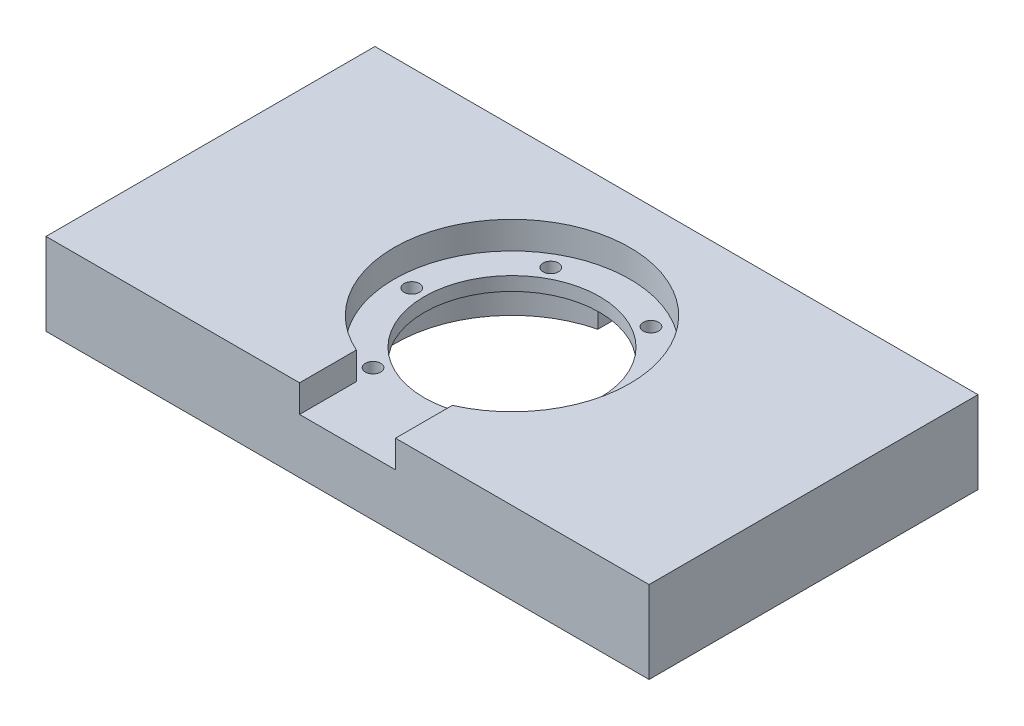
SolidWorks part; units mm, degrees
ref_plane "Front Plane" through (0, 0, 0) normal (0, 0, 1) x (1, 0, 0)
ref_plane "Top Plane" through (0, 0, 0) normal (0, 1, 0) x (1, 0, 0)
ref_plane "Right Plane" through (0, 0, 0) normal (1, 0, 0) x (0, 0, -1)
sketch "Sketch1" plane through (0, 0, 0) normal (0, 1, 0) x (1, 0, 0)
  line L1 (110, -60) -> (-110, -60)
  line L2 (110, -60) -> (110, 60)
  line L3 (110, 60) -> (-110, 60)
  line L4 (-110, -60) -> (-110, 60)
  line L5 (110, -60) -> (-110, 60) construction
  line L6 (110, 60) -> (-110, -60) construction
  circle A0 centre (0, 0) radius 43
  dimension "D1" = 86
  dimension "D2" = 120
  dimension "D3" = 220
extrude "Boss-Extrude1" add sketch "Sketch1" along normal blind 10
sketch "Sketch2" plane through (0, 0, 0) normal (0, -1, 0) x (1, 0, 0)
  line L1 (-110, 60) -> (110, 60)
  line L2 (-110, 60) -> (-110, -60)
  line L3 (-110, -60) -> (110, -60)
  line L4 (110, 60) -> (110, -60)
  circle A0 centre (18.1221, 32.2581) radius 2.8
  circle A1 centre (36.9974, 0.4348) radius 2.8
  circle A2 centre (18.8753, -31.8233) radius 2.8
  circle A3 centre (-18.1221, -32.2581) radius 2.8
  circle A4 centre (-36.9974, -0.4348) radius 2.8
  circle A5 centre (-18.8753, 31.8233) radius 2.8
  point P21 (0, 0)
  dimension "D1" = 5.6
  dimension "D2" = 37
  dimension "D3" = 6
extrude "Boss-Extrude2" add sketch "Sketch2" along normal blind 20
sketch "Sketch3" plane through (0, 0, 60) normal (0, 0, 1) x (1, 0, 0)
  line L0 (-110, 10) -> (110, 10) construction
  line L1 (-17.5, 0) -> (17.5, 0)
  line L2 (-17.5, 0) -> (-17.5, 10)
  line L3 (-17.5, 10) -> (17.5, 10)
  line L4 (17.5, 0) -> (17.5, 10)
  line L5 (-17.5, 0) -> (17.5, 10) construction
  line L6 (-17.5, 10) -> (17.5, 0) construction
  point P0 (0, 5)
  dimension "D1" = 35
  dimension "D2" = 10
extrude "Cut-Extrude1" cut sketch "Sketch3" against normal up to next
sketch "Sketch4" plane through (0, 0, 0) normal (0, 1, 0) x (1, 0, 0)
  circle A0 centre (0, 0) radius 32
  dimension "D1" = 64
extrude "Cut-Extrude2" cut sketch "Sketch4" against normal through all
sketch "Sketch5" plane through (0, 0, -60) normal (0, 0, -1) x (-1, 0, 0)
  line L0 (110, -20) -> (-110, -20) construction
  line L1 (-10, -10) -> (10, -10)
  line L2 (-10, -10) -> (-10, -20)
  line L3 (-10, -20) -> (10, -20)
  line L4 (10, -10) -> (10, -20)
  line L5 (-10, -10) -> (10, -20) construction
  line L6 (-10, -20) -> (10, -10) construction
  point P0 (0, -15)
  dimension "D1" = 20
  dimension "D2" = 10
extrude "Cut-Extrude3" cut sketch "Sketch5" against normal up to next
sketch "Sketch6" plane through (0, -20, 0) normal (0, -1, 0) x (1, 0, 0)
  circle A1 centre (0, 0) radius 42.5
  dimension "D1" = 85
extrude "Cut-Extrude4" cut sketch "Sketch6" against normal blind 15
